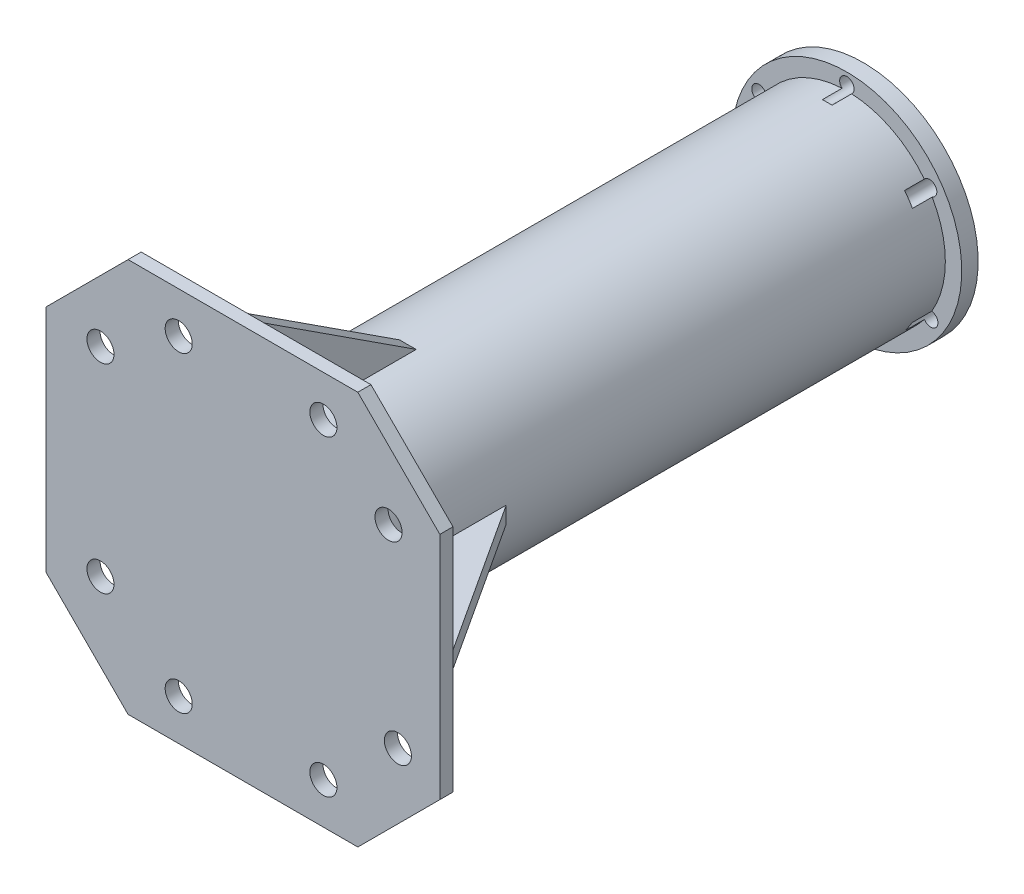
SolidWorks part; units mm, degrees
ref_plane "Front Plane" through (0, 0, 0) normal (0, 0, 1) x (1, 0, 0)
ref_plane "Top Plane" through (0, 0, 0) normal (0, 1, 0) x (1, 0, 0)
ref_plane "Right Plane" through (0, 0, 0) normal (1, 0, 0) x (0, 0, -1)
sketch "Sketch2" plane through (0, 0, 0) normal (0, 0, 1) x (1, 0, 0)
  circle A0 centre (0, 0) radius 60
  dimension "D1" = 120
extrude "Boss-Extrude1" add sketch "Sketch2" along normal blind 360
sketch "Sketch3" plane through (0, 0, 0) normal (0, 0, -1) x (-1, 0, 0)
  circle A1 centre (0, 0) radius 70
  dimension "D1" = 140
extrude "Boss-Extrude2" add sketch "Sketch3" along normal blind 10
sketch "Sketch4" plane through (0, 0, 360) normal (0, 0, 1) x (1, 0, 0)
  line L0 (-70, 120) -> (-120, 70)
  line L1 (70, 120) -> (-70, 120)
  line L2 (120, 70) -> (120, -70)
  line L3 (70, -120) -> (-70, -120)
  line L4 (-120, 70) -> (-120, -70)
  line L5 (120, 120) -> (-120, -120) construction
  line L6 (120, -120) -> (-120, 120) construction
  line L7 (-70, -120) -> (-120, -70)
  line L8 (120, 70) -> (70, 120)
  line L9 (120, -70) -> (70, -120)
  point P4 (0, 0)
  dimension "D1" = 240
  dimension "D2" = 240
extrude "Boss-Extrude4" add sketch "Sketch4" along normal blind 8
sketch "Sketch5" plane through (0, 0, 368) normal (0, 0, 1) x (1, 0, 0)
  line L5 (-47.3957, -95) -> (-45.866, -95)
  circle A0 centre (-39.1457, 95) radius 8.25
  circle A1 centre (-39.1457, -95) radius 8.25
  circle A2 centre (49.0204, 95) radius 8.25
  circle A3 centre (49.0204, -95) radius 8.25
  point P0 (0, 0)
  dimension "D2" = 16.5
  dimension "D3" = 16.5
  dimension "D4" = 16.5
  dimension "D5" = 16.5
sketch "Sketch7" plane through (0, 0, 0) normal (1, 0, 0) x (0, 0, -1)
  line L0 (-360, -120) -> (-260, -55)
  line L1 (-260, -55) -> (-360, -55)
  line L2 (-360, -60) -> (-360, 60) construction
  line L3 (-360, -55) -> (-360, -120)
  point P3 (-260, -55)
  dimension "D1" = 65
  dimension "D2" = 100
extrude "Boss-Extrude5" add sketch "Sketch7" along normal mid plane 10
pattern_circular "CirPattern1" count 4 over 360 about axis through (0, 0, 0) along (0, 0, 1) of "Boss-Extrude5"
extrude "Cut-Extrude2" cut sketch "Sketch5" against normal blind 10 contours A1 | A0 | A3 | A2
sketch "Sketch8" plane through (0, 0, 368) normal (0, 0, 1) x (1, 0, 0)
  circle A0 centre (-86.8081, 65.6412) radius 8.25
  circle A1 centre (-86.8081, -55.6523) radius 8.25
  circle A2 centre (94.4186, -55.6523) radius 8.25
  circle A3 centre (88.7107, 59.4576) radius 8.25
  point P8 (0, 0)
  dimension "D1" = 16.5
  dimension "D2" = 16.5
  dimension "D3" = 16.5
  dimension "D4" = 16.5
extrude "Cut-Extrude3" cut sketch "Sketch8" against normal blind 10
sketch "Sketch9" plane through (0, 0, -10) normal (0, 0, -1) x (-1, 0, 0)
  circle A0 centre (0, 63.2047) radius 4.4
  circle A1 centre (1.291, -53.6705) radius 4.4
  circle A2 centre (53.5623, 32.2836) radius 4.4
  circle A3 centre (-50.4266, 34.1017) radius 4.4
  circle A4 centre (52.7693, -32.9342) radius 4.4
  circle A5 centre (-51.0845, -34.7169) radius 4.4
  point P12 (44.4166, -33.1296)
  point P13 (0, 0)
  point P14 (-48.1392, 37.5327)
  point P15 (0, 64.2507)
  point P16 (0, -64.4086)
  point P17 (0, 63.2047)
  point P18 (0, 0)
  point P19 (0, 0)
  point P20 (0, 0)
  point P21 (0, 0)
  dimension "D1" = 8.8
  dimension "D3" = 8.8
  dimension "D4" = 8.8
  dimension "D5" = 8.8
  dimension "D6" = 8.8
  dimension "D2" = 2
extrude "Cut-Extrude8" cut sketch "Sketch9" against normal blind 22 and the other way blind 25
